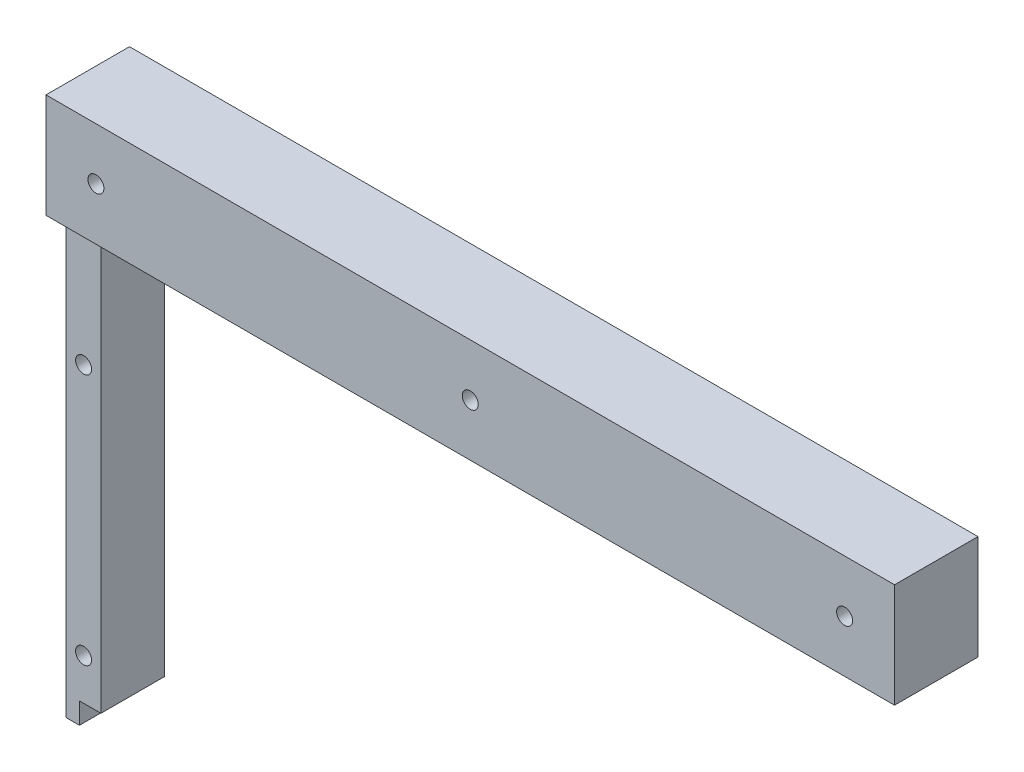
SolidWorks part; units mm, degrees
ref_plane "Front" through (0, 0, 0) normal (0, 0, 1) x (1, 0, 0)
ref_plane "Top" through (0, 0, 0) normal (0, 1, 0) x (1, 0, 0)
ref_plane "Right" through (0, 0, 0) normal (1, 0, 0) x (0, 0, -1)
sketch "Szkic1" plane through (0, 0, 0) normal (0, 0, 1) x (1, 0, 0)
  line L1 (-42.3157, 17.2415) -> (6.4506, 17.2415)
  line L2 (-42.3157, 17.2415) -> (-42.3157, 7.8059)
  line L3 (-42.3157, 7.8059) -> (6.4506, 7.8059)
  line L4 (6.4506, 17.2415) -> (6.4506, 7.8059)
extrude "Dodanie-wyciągnięcie1" add sketch "Szkic1" along normal blind 10
sketch "Szkic2" plane through (0, 0, 10) normal (0, 0, 1) x (1, 0, 0)
  line L1 (6.4506, 17.2415) -> (-42.3157, 17.2415)
  line L2 (6.4506, 17.2415) -> (6.4506, 7.8059)
  line L3 (6.4506, 7.8059) -> (-42.3157, 7.8059)
  line L4 (-42.3157, 17.2415) -> (-42.3157, 7.8059)
extrude "Dodanie-wyciągnięcie2" add sketch "Szkic2" along normal blind 2
sketch "Szkic5" plane through (-42.3157, 0, 0) normal (-1, 0, 0) x (0, 0, 1)
  line L1 (12, 17.2415) -> (0, 17.2415)
  line L2 (12, 17.2415) -> (12, 7.8059)
  line L3 (12, 7.8059) -> (0, 7.8059)
  line L4 (0, 17.2415) -> (0, 7.8059)
extrude "Dodanie-wyciągnięcie3" add sketch "Szkic5" along normal up to surface (73.2336 mm away)
sketch "Szkic6" plane through (0, 17.2415, 0) normal (0, 1, 0) x (1, 0, 0)
  line L1 (-115.5494, -12) -> (6.4506, -12)
  line L2 (-115.5494, -12) -> (-115.5494, 0)
  line L3 (-115.5494, 0) -> (6.4506, 0)
  line L4 (6.4506, -12) -> (6.4506, 0)
extrude "Dodanie-wyciągnięcie4" add sketch "Szkic6" along normal up to vertex (5.5644 mm away)
sketch "Szkic7" plane through (0, 7.8059, 0) normal (0, -1, 0) x (1, 0, 0)
  line L0 (-115.5494, 12) -> (6.4506, 12) construction
  line L1 (-115.5494, 0) -> (-112.1448, 0)
  line L2 (-115.5494, 0) -> (-115.5494, 12)
  line L3 (-115.5494, 12) -> (-112.1448, 12)
  line L4 (-112.1448, 0) -> (-112.1448, 12)
extrude "Dodanie-wyciągnięcie5" add sketch "Szkic7" along normal up to vertex (64 mm away)
sketch "Szkic8" plane through (-112.1448, 0, 0) normal (1, 0, 0) x (0, 0, -1)
  line L0 (-12, -56.1941) -> (-12, 7.8059) construction
  line L1 (0, -56.1941) -> (-12, -56.1941)
  line L2 (0, -56.1941) -> (0, -53.1451)
  line L3 (0, -53.1451) -> (-12, -53.1451)
  line L4 (-12, -56.1941) -> (-12, -53.1451)
extrude "Wytnij-wyciągnięcie1" cut sketch "Szkic8" against normal blind 1.5
sketch "Szkic9" plane through (0, 0, 12) normal (0, 0, 1) x (1, 0, 0)
  line L0 (-54.5494, 22.8059) -> (-54.5494, 0) construction
  line L1 (-115.5494, 22.8059) -> (6.4506, 22.8059) construction
  line L2 (6.4506, 15.3059) -> (-115.5494, 15.3059) construction
  line L3 (6.4506, 7.8059) -> (6.4506, 22.8059) construction
  line L4 (-115.5494, 22.8059) -> (-115.5494, -56.1941) construction
  circle A0 centre (-54.5494, 15.3059) radius 1.15
  circle A1 centre (-108.374, 15.3059) radius 1.15
  circle A2 centre (-0.7248, 15.3059) radius 1.15
extrude "Wytnij-wyciągnięcie2" cut sketch "Szkic9" against normal through all
sketch "Szkic10" plane through (-112.1448, 0, 0) normal (1, 0, 0) x (0, 0, -1)
  line L1 (-12, -53.1451) -> (0, -53.1451)
  line L2 (-12, -53.1451) -> (-12, 7.8059)
  line L3 (-12, 7.8059) -> (0, 7.8059)
  line L4 (0, -53.1451) -> (0, 7.8059)
extrude "Dodanie-wyciągnięcie6" add sketch "Szkic10" along normal blind 1.6
sketch "Szkic11" plane through (0, 0, 12) normal (0, 0, 1) x (1, 0, 0)
  line L0 (-110.5448, 7.8059) -> (-115.5494, 7.8059) construction
  line L1 (-115.5494, 22.8059) -> (-115.5494, -56.1941) construction
  line L2 (-113.0471, 7.8059) -> (-113.0471, -53.1451) construction
  line L3 (-113.6448, -53.1451) -> (-110.5448, -53.1451) construction
  circle A0 centre (-113.0471, -47.1994) radius 1.15
  circle A1 centre (-113.0471, -10.9968) radius 1.15
  dimension "D1" = 2.3
  dimension "D2" = 2.3
extrude "Wytnij-wyciągnięcie3" cut sketch "Szkic11" against normal through all
sketch "Szkic12" plane through (-115.5494, 0, 0) normal (-1, 0, 0) x (0, 0, 1)
  line L0 (12, 22.8059) -> (12, -56.1941) construction
  line L1 (9.1, 7.8059) -> (12, 7.8059)
  line L2 (9.1, 7.8059) -> (9.1, -56.1941)
  line L3 (9.1, -56.1941) -> (12, -56.1941)
  line L4 (12, 7.8059) -> (12, -56.1941)
extrude "Wytnij-wyciągnięcie4" cut sketch "Szkic12" against normal up to surface (5.0046 mm away) up to face at (-110.5448, -22.6696, 6)
